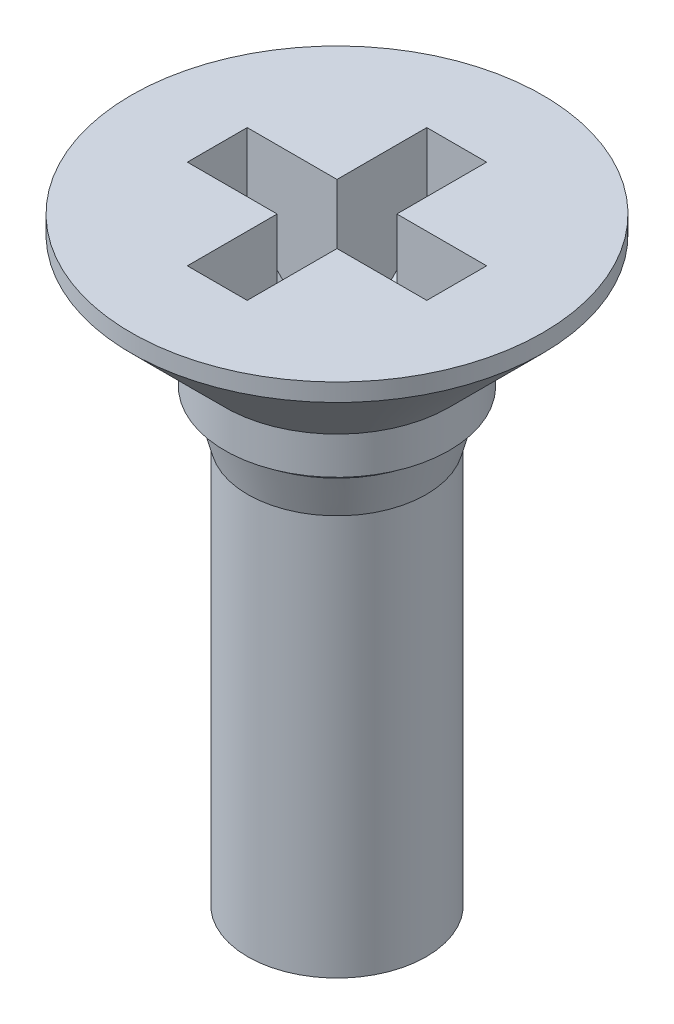
SolidWorks part; units mm, degrees
ref_plane "Vorderseite" through (0, 0, 0) normal (0, 0, 1) x (1, 0, 0)
ref_plane "Oben" through (0, 0, 0) normal (0, 1, 0) x (1, 0, 0)
ref_plane "Rechts" through (0, 0, 0) normal (1, 0, 0) x (0, 0, -1)
sketch "Skizze1" plane through (0, 0, 0) normal (0, 0, 1) x (1, 0, 0)
  line L0 (0, 0) -> (2.75, 0)
  line L1 (2.75, 0) -> (2.75, -0.2375)
  line L2 (2.75, -0.2375) -> (1.5, -1.4875)
  line L3 (1.3375, -1.9875) -> (1.3375, -2.1126)
  line L4 (1.3375, -2.1126) -> (1.1935, -2.65)
  line L5 (1.1935, -2.65) -> (1.1935, -8)
  line L6 (1.1935, -8) -> (0, -8)
  line L7 (0, 0) -> (0, -8) construction
  line L8 (0, 0) -> (0, -8)
  line L10 (1.5, -1.4875) -> (1.5, -1.9875)
  line L12 (1.5, -1.9875) -> (1.3375, -1.9875)
  point P3 (1.3375, -1.65)
  dimension "D1" = 45
  dimension "D2" = 15
  dimension "K" = 1.65
  dimension "DA" = 5.5
  dimension "DK" = 2.387
  dimension "L" = 8
  dimension "DG" = 3
  dimension "A" = 1
  dimension "DF" = 2.675
  dimension "P" = 0.5
revolve "Basis-Rotation" add sketch "Skizze1" angle 360 about L7
sketch "Skizze2" plane through (0, 0, 0) normal (0, 0, 1) x (1, 0, 0)
  line L0 (0, -2.1) -> (0, 0) construction
  line L1 (0, 0) -> (0, -8) construction
  line L2 (-0.55, -2.1) -> (0.55, -2.1)
  line L3 (1.6, 0) -> (1.6, -1.05)
  line L4 (1.6, -1.05) -> (0.55, -2.1)
  line L5 (1.6, 0) -> (-1.6, 0)
  line L6 (-1.6, -1.05) -> (-0.55, -2.1)
  line L7 (-1.6, 0) -> (-1.6, -1.05)
  line L8 (0, -1.05) -> (1.6, -1.05) construction
  line L9 (2.75, 0) -> (-2.75, 0) construction
  line L11 (1.5, -1.4875) -> (2.75, -0.2375) construction
  point P11 (0, 0)
  dimension "M" = 3.2
  dimension "T" = 2.1
extrude "Kreuzschlitz1 H" cut sketch "Skizze2" against normal blind 0.4 and the other way blind 0.4
sketch "Skizze3" plane through (0, 0, 0) normal (1, 0, 0) x (0, 0, -1)
  line L0 (0, -2.1) -> (0, 0) construction
  line L2 (-0.55, -2.1) -> (0.55, -2.1)
  line L3 (1.6, 0) -> (1.6, -1.05)
  line L4 (1.6, -1.05) -> (0.55, -2.1)
  line L5 (1.6, 0) -> (-1.6, 0)
  line L6 (-1.6, -1.05) -> (-0.55, -2.1)
  line L7 (-1.6, 0) -> (-1.6, -1.05)
  line L8 (0, -1.05) -> (1.6, -1.05) construction
  point P11 (0, 0)
extrude "Kreuzschlitz2 H" cut sketch "Skizze3" against normal blind 0.4 and the other way blind 0.4
sketch "Skizze4" plane through (2.4522, 0, -1.8507) normal (0, 1, 0) x (-1, 0, 0)
  line L0 (7.3522, 1.8507) -> (-2.4478, 1.8507) construction
  line L1 (2.4522, -3.0493) -> (2.4522, 6.7507) construction
  line L2 (-2.4478, 1.0342) -> (-2.4478, 2.6672)
  line L3 (-2.4478, 1.0342) -> (0.0059, 1.0342)
  line L4 (0.0059, 1.0342) -> (0.8191, 0.6258)
  line L5 (1.2273, 0.2176) -> (-1.0126, -1.6141)
  line L6 (0.8191, 0.6258) -> (-1.0126, -1.6141)
  line L7 (1.6357, -0.5956) -> (1.2273, 0.2176)
  line L8 (1.6357, -3.0493) -> (1.6357, -0.5956)
  line L9 (1.6357, -3.0493) -> (3.2687, -3.0493)
  line L10 (3.2687, -3.0493) -> (3.2687, -0.5956)
  line L11 (3.2687, -0.5956) -> (3.6772, 0.2176)
  line L12 (2.4522, 1.8507) -> (-1.0126, -1.6141) construction
  line L13 (4.0854, 0.6258) -> (5.917, -1.6141)
  line L14 (3.6772, 0.2176) -> (5.917, -1.6141)
  line L15 (4.8986, 1.0342) -> (4.0854, 0.6258)
  line L16 (7.3522, 1.0342) -> (4.8986, 1.0342)
  line L17 (7.3522, 1.0342) -> (7.3522, 2.6672)
  line L18 (7.3522, 2.6672) -> (4.8986, 2.6672)
  line L19 (4.8986, 2.6672) -> (4.0854, 3.0757)
  line L20 (3.6772, 3.4839) -> (5.917, 5.3156)
  line L21 (4.0854, 3.0757) -> (5.917, 5.3156)
  line L22 (3.2687, 4.2971) -> (3.6772, 3.4839)
  line L23 (3.2687, 6.7507) -> (3.2687, 4.2971)
  line L24 (1.6357, 6.7507) -> (3.2687, 6.7507)
  line L25 (1.6357, 6.7507) -> (1.6357, 4.2971)
  line L26 (1.6357, 4.2971) -> (1.2273, 3.4839)
  line L27 (0.8191, 3.0757) -> (-1.0126, 5.3156)
  line L28 (1.2273, 3.4839) -> (-1.0126, 5.3156)
  line L29 (0.0059, 2.6672) -> (0.8191, 3.0757)
  line L30 (-2.4478, 2.6672) -> (0.0059, 2.6672)
  circle A0 centre (2.4522, 1.8507) radius 4.9 construction
  circle A1 centre (2.4522, 1.8507) radius 2.0415 construction
  circle A2 centre (2.4522, 1.8507) radius 2.579 construction
  dimension "X2" = 4.083
  dimension "X1" = 5.158
  dimension "M" = 9.8
  dimension "D3" = 5.725
  dimension "X3" = 1.633
